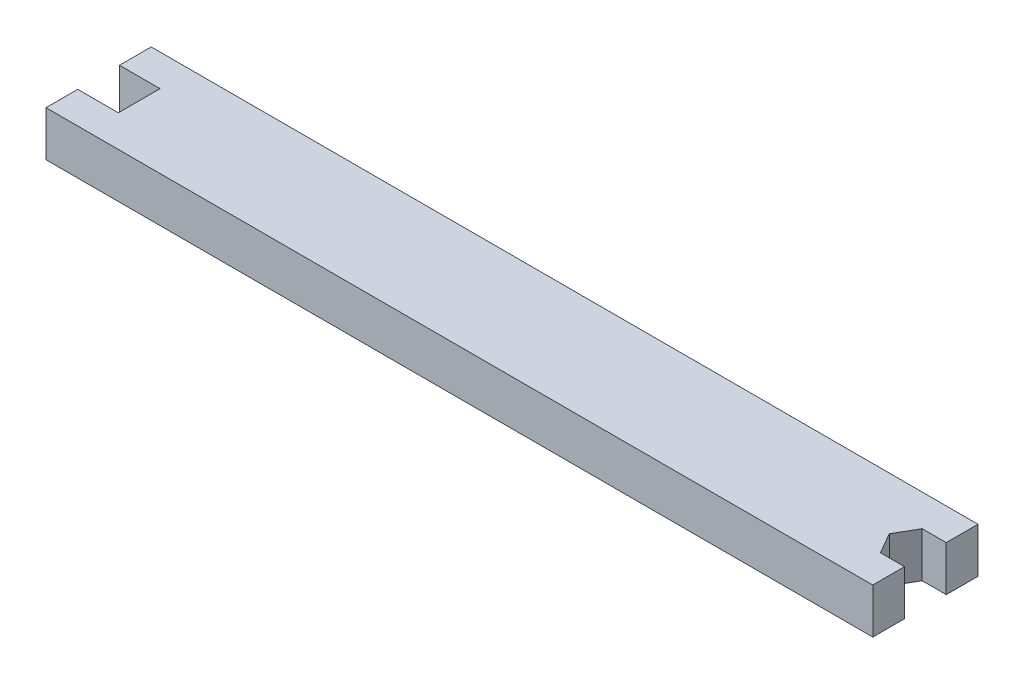
SolidWorks part; units mm, degrees
ref_plane "Płaszczyzna przednia" through (0, 0, 0) normal (0, 0, 1) x (1, 0, 0)
ref_plane "Płaszczyzna górna" through (0, 0, 0) normal (0, 1, 0) x (1, 0, 0)
ref_plane "Płaszczyzna prawa" through (0, 0, 0) normal (1, 0, 0) x (0, 0, -1)
sketch "Szkic1" plane through (0, 0, 0) normal (0, 1, 0) x (1, 0, 0)
  line L0 (0, -82.2413) -> (0, -96.2413)
  line L1 (0, -82.2413) -> (110, -82.2413)
  line L2 (0, -96.2413) -> (110, -96.2413)
  line L3 (110, -82.2413) -> (110, -96.2413)
  dimension "D1" = 14
  dimension "D2" = 110
extrude "Dodanie-wyciągnięcie1" add sketch "Szkic1" along normal blind 6
sketch "Szkic2" plane through (0, 6, 0) normal (0, 1, 0) x (1, 0, 0)
  line L0 (0, -86.4663) -> (5.4, -86.4663)
  line L1 (0, -86.4663) -> (0, -92.0163)
  line L2 (5.4, -86.4663) -> (5.4, -92.0163)
  line L3 (0, -92.0163) -> (5.4, -92.0163)
  line L4 (0, -82.2413) -> (0, -96.2413) construction
  line L5 (0, -96.2413) -> (110, -96.2413) construction
  point P6 (0, -89.2413)
  dimension "D1" = 7
  dimension "D2" = 5.55
  dimension "D3" = 5.4
extrude "Wytnij-wyciągnięcie1" cut sketch "Szkic2" against normal blind 6
sketch "Szkic3" plane through (0, 6, 0) normal (0, 1, 0) x (1, 0, 0)
  line L0 (0, -96.2413) -> (110, -96.2413) construction
  line L1 (106.7957, -92.0163) -> (110, -92.0163)
  line L2 (110, -92.0163) -> (111.6021, -89.2413)
  line L3 (111.6021, -89.2413) -> (110, -86.4663)
  line L4 (110, -86.4663) -> (106.7957, -86.4663)
  line L5 (106.7957, -86.4663) -> (105.1936, -89.2413)
  line L6 (105.1936, -89.2413) -> (106.7957, -92.0163)
  line L7 (110, -96.2413) -> (110, -82.2413) construction
  circle A0 centre (108.3979, -89.2413) radius 2.775 construction
  dimension "D3" = 7
  dimension "D1" = 0
  dimension "D2" = 0
extrude "Wytnij-wyciągnięcie2" cut sketch "Szkic3" against normal blind 6
